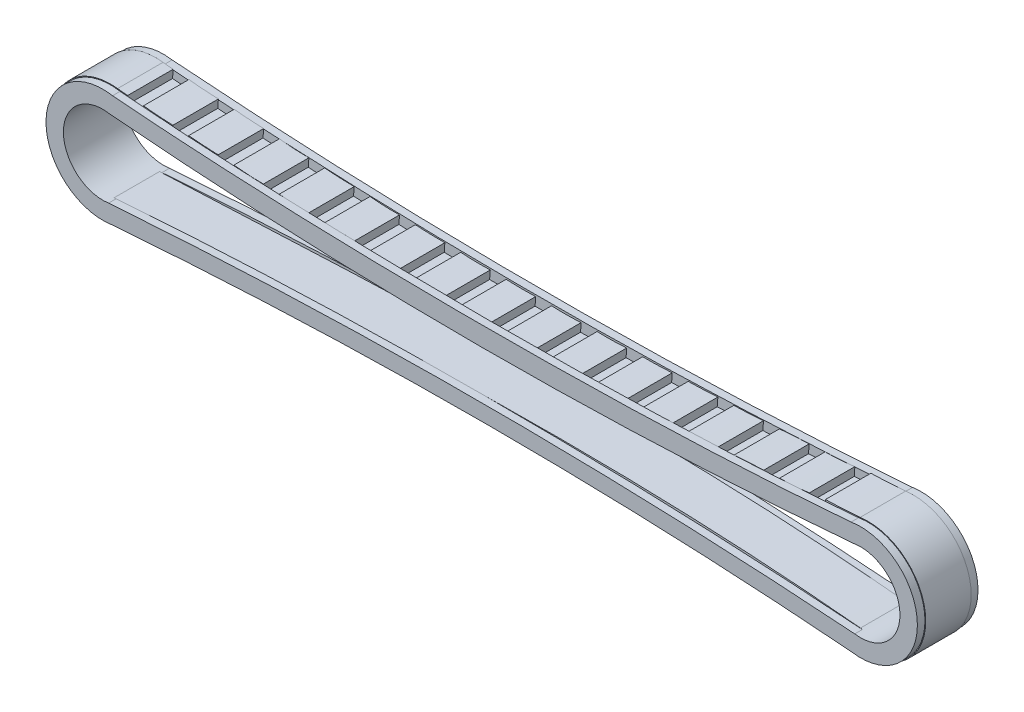
SolidWorks part; units mm, degrees
ref_plane "Front Plane" through (0, 0, 0) normal (0, 0, 1) x (1, 0, 0)
ref_plane "Top Plane" through (0, 0, 0) normal (0, 1, 0) x (1, 0, 0)
ref_plane "Right Plane" through (0, 0, 0) normal (1, 0, 0) x (0, 0, -1)
sketch "Sketch2" plane through (0, 0, 0) normal (0, 0, 1) x (1, 0, 0)
  line L0 (-1229.0453, 0) -> (-23.5148, 0) construction
  line L1 (0, 91.9794) -> (0, -97.7402) construction
  line L2 (-238.5868, 37.1013) -> (-238.9988, 31.5696)
  line L3 (-19.0453, 21.1981) -> (-19.0453, 24.4396)
  line L4 (-228.5815, 30.8004) -> (-228.1726, 36.4078)
  line L5 (-79.0453, 22.4891) -> (-79.0453, 24.4396)
  line L6 (-49.0453, 21.6706) -> (-49.0453, 24.4396)
  line L7 (10.9547, 21.0829) -> (10.9547, 24.4396)
  line L8 (-0.2495, 14.7795) -> (-0.2496, 14.7776)
  line L9 (130.9547, 24.1644) -> (130.9547, 24.4396)
  line L10 (-208.7416, 35.0228) -> (-209.1594, 29.4132)
  line L11 (-198.7348, 28.6971) -> (-198.3256, 34.3091)
  line L12 (40.9547, 21.3284) -> (40.9547, 24.4396)
  line L13 (70.9547, 21.9309) -> (70.9547, 24.4396)
  line L14 (100.9547, 22.8809) -> (100.9547, 24.4396)
  line L15 (-178.8894, 33.0384) -> (-179.3077, 27.4231)
  line L16 (-168.875, 26.7748) -> (-168.4653, 32.393)
  line L17 (-246.0886, 25.7041) -> (245.6238, 25.6291) construction
  line L18 (-245.2661, 37.704) -> (244.7044, 37.6292) construction
  line L19 (-247.5881, -25.8879) -> (244.925, -25.4999) construction
  line L20 (-149.0216, 31.2639) -> (-149.4404, 25.6411)
  line L21 (-138.999, 25.0749) -> (-138.5887, 30.7013)
  line L22 (-109.0453, 23.6339) -> (-109.0453, 24.4396)
  line L23 (-119.4727, 25.2083) -> (-119.5547, 24.1072)
  line L24 (-247.0779, -37.8875) -> (243.8604, -37.5007) construction
  line L25 (-119.1351, 29.7397) -> (-119.4727, 25.2083)
  line L26 (-109.0453, 24.4396) -> (-108.6928, 29.2733)
  line L27 (221.3507, -29.8697) -> (221.8274, -36.4078)
  line L28 (-89.4727, 25.2083) -> (-89.6477, 22.8577)
  line L29 (211.2517, -34.9327) -> (210.8153, -29.0737)
  line L30 (-89.2273, 28.5023) -> (-89.4727, 25.2083)
  line L31 (-79.0453, 24.4396) -> (-78.7752, 28.1435)
  line L32 (191.1909, -27.6789) -> (191.617, -33.5219)
  line L33 (-59.4727, 25.2083) -> (-59.7174, 21.923)
  line L34 (181.0939, -32.8144) -> (180.6592, -26.979)
  line L35 (-59.2958, 27.5822) -> (-59.4727, 25.2083)
  line L36 (-49.0453, 24.4396) -> (-48.8338, 27.34)
  line L37 (161.0517, -25.7703) -> (161.4761, -31.5895)
  line L38 (-29.4727, 25.2083) -> (-29.7618, 21.3263)
  line L39 (150.9576, -30.9848) -> (150.5273, -25.2083)
  line L40 (-29.339, 27.0024) -> (-29.4727, 25.2083)
  line L41 (-19.0453, 24.4396) -> (-18.8671, 26.8832)
  line L42 (10.9547, 14.7776) -> (10.9547, 14.7844)
  line L43 (0.5273, 25.2083) -> (0.22, 21.0827)
  line L44 (-0.2496, 14.7776) -> (10.9547, 14.7776)
  line L45 (0.6443, 26.7781) -> (0.5273, 25.2083)
  line L46 (10.9547, 24.4396) -> (11.1257, 26.7849)
  line L47 (150.5273, -25.2083) -> (150.5248, -25.1736)
  line L48 (30.5273, 25.2083) -> (30.2287, 21.1993)
  line L49 (130.9547, -24.4396) -> (131.3571, -29.9585)
  line L50 (30.6545, 26.9158) -> (30.5273, 25.2083)
  line L51 (40.9547, 24.4396) -> (41.145, 27.0493)
  line L52 (120.8443, -29.4634) -> (120.5273, -25.2083)
  line L53 (60.5273, 25.2083) -> (60.2642, 21.6757)
  line L54 (120.5273, -25.2083) -> (120.4132, -23.6764)
  line L55 (60.6917, 27.4148) -> (60.5273, 25.2083)
  line L56 (70.9547, 24.4396) -> (71.1905, 27.6732)
  line L57 (100.9547, -24.4396) -> (101.2615, -28.6474)
  line L58 (90.5273, 25.2083) -> (90.326, 22.5053)
  line L59 (90.7553, -28.2681) -> (90.5273, -25.2083)
  line L60 (90.7553, 28.2681) -> (90.5273, 25.2083)
  line L61 (100.9547, 24.4396) -> (101.2615, 28.6474)
  line L62 (90.5273, -25.2083) -> (90.326, -22.5053)
  line L63 (120.5273, 25.2083) -> (120.4132, 23.6764)
  line L64 (70.9547, -24.4396) -> (71.1905, -27.6732)
  line L65 (120.8443, 29.4634) -> (120.5273, 25.2083)
  line L66 (130.9547, 24.4396) -> (131.3571, 29.9585)
  line L67 (60.6917, -27.4148) -> (60.5273, -25.2083)
  line L68 (150.5273, 25.2083) -> (150.5248, 25.1736)
  line L69 (60.5273, -25.2083) -> (60.2642, -21.6757)
  line L70 (150.9576, 30.9848) -> (150.5273, 25.2083)
  line L71 (161.0517, 25.7703) -> (161.4761, 31.5895)
  line L72 (40.9547, -24.4396) -> (41.145, -27.0493)
  line L73 (30.6545, -26.9158) -> (30.5273, -25.2083)
  line L74 (30.5273, -25.2083) -> (30.2287, -21.1993)
  line L75 (181.0939, 32.8144) -> (180.6592, 26.979)
  line L76 (191.1909, 27.6789) -> (191.617, 33.5219)
  line L77 (10.9547, -24.4396) -> (11.1257, -26.7849)
  line L78 (0.6443, -26.7781) -> (0.5273, -25.2083)
  line L79 (-0.2496, -14.7776) -> (0, -14.7776)
  line L80 (211.2517, 34.9327) -> (210.8153, 29.0737)
  line L81 (221.3507, 29.8697) -> (221.8274, 36.4078)
  line L82 (221.3507, -29.8697) -> (221.8274, -36.4078)
  line L83 (0.5273, -25.2083) -> (0.22, -21.0827)
  line L84 (-245.2661, -37.704) -> (-247.0779, -37.8875)
  line L85 (10.9547, -14.7776) -> (10.9547, -14.7844)
  line L87 (-19.0453, -24.4396) -> (-18.8671, -26.8832)
  line L88 (-29.339, -27.0024) -> (-29.4727, -25.2083)
  line L89 (-29.4727, -25.2083) -> (-29.7618, -21.3263)
  line L90 (-49.0453, -24.4396) -> (-48.8338, -27.34)
  line L91 (-59.2958, -27.5822) -> (-59.4727, -25.2083)
  line L92 (-59.4727, -25.2083) -> (-59.7174, -21.923)
  line L93 (-79.0453, -24.4396) -> (-78.7752, -28.1435)
  line L94 (-89.2273, -28.5023) -> (-89.4727, -25.2083)
  line L95 (-89.4727, -25.2083) -> (-89.6477, -22.8577)
  line L96 (-109.0453, -24.4396) -> (-108.6928, -29.2733)
  line L97 (-119.1351, -29.7397) -> (-119.4727, -25.2083)
  line L98 (-119.4727, -25.2083) -> (-119.5547, -24.1072)
  line L99 (-109.0453, -23.6339) -> (-109.0453, -24.4396)
  line L100 (-138.999, -25.0749) -> (-138.5887, -30.7013)
  line L101 (-149.0216, -31.2639) -> (-149.4404, -25.6411)
  line L102 (-168.875, -26.7748) -> (-168.4653, -32.393)
  line L103 (-178.8894, -33.0384) -> (-179.3077, -27.4231)
  line L104 (100.9547, -22.8809) -> (100.9547, -24.4396)
  line L105 (70.9547, -21.9309) -> (70.9547, -24.4396)
  line L106 (40.9547, -21.3284) -> (40.9547, -24.4396)
  line L107 (-198.7348, -28.6971) -> (-198.3256, -34.3091)
  line L108 (-208.7416, -35.0228) -> (-209.1594, -29.4132)
  line L109 (130.9547, -24.1644) -> (130.9547, -24.4396)
  line L110 (-0.2495, -14.7795) -> (-0.2496, -14.7776)
  line L111 (10.9547, -21.0829) -> (10.9547, -24.4396)
  line L112 (-49.0453, -21.6706) -> (-49.0453, -24.4396)
  line L113 (-79.0453, -22.4891) -> (-79.0453, -24.4396)
  line L114 (-228.5815, -30.8004) -> (-228.1726, -36.4078)
  line L115 (-19.0453, -21.1981) -> (-19.0453, -24.4396)
  line L116 (-238.5868, -37.1013) -> (-238.9988, -31.5696)
  arc A0 (-246.0886, 25.7041) -> (-247.5881, -25.8879) centre (-250, 0) ccw
  arc A1 (245.6238, 25.6291) -> (244.925, -25.4999) centre (250, 0) cw
  arc A2 (244.7044, 37.6292) -> (243.8604, -37.5007) centre (250, 0) cw
  arc A3 (-245.2661, 37.704) -> (-247.0779, -37.8875) centre (-250, 0) ccw
  arc A4 (-245.2661, 37.704) -> (-238.5868, 37.1013) centre (-233.2976, 133.0299) ccw
  arc A5 (-228.1726, 36.4078) -> (-208.7416, 35.0228) centre (-200.4416, 288.4609) ccw
  arc A6 (-198.3256, 34.3091) -> (-178.8894, 33.0384) centre (-168.3509, 343.5164) ccw
  arc A7 (-168.4653, 32.393) -> (-149.0216, 31.2639) centre (-148.9074, 201.2136) ccw
  arc A8 (-138.5887, 30.7013) -> (-119.1351, 29.7397) centre (-117.6946, 256.1426) ccw
  arc A9 (-108.6928, 29.2733) -> (-89.2273, 28.5023) centre (-91.9581, 205.6706) ccw
  arc A10 (-78.7752, 28.1435) -> (-59.2958, 27.5822) centre (-61.3802, 293.5168) ccw
  arc A11 (-48.8338, 27.34) -> (-29.339, 27.0024) centre (-35.9794, 206.5986) ccw
  arc A12 (-18.8671, 26.8832) -> (0.6443, 26.7781) centre (-7.8548, 260.1471) ccw
  arc A13 (11.1257, 26.7849) -> (30.6545, 26.9158) centre (19.9046, 173.9124) ccw
  arc A14 (41.145, 27.0493) -> (60.6917, 27.4148) centre (47.6506, 201.9714) ccw
  arc A15 (71.1905, 27.6732) -> (90.7553, 28.2681) centre (72.8619, 294.7119) ccw
  arc A16 (101.2615, 28.6474) -> (120.8443, 29.4634) centre (96.1057, 387.8004) ccw
  arc A17 (131.3571, 29.9585) -> (150.9576, 30.9848) centre (123.4328, 368.9588) ccw
  arc A18 (161.4761, 31.5895) -> (181.0939, 32.8144) centre (199.5593, -420.6439) cw
  arc A19 (191.617, 33.5219) -> (211.2517, 34.9327) centre (191.5828, 171.3394) ccw
  arc A20 (221.8274, 36.4078) -> (244.7044, 37.6292) centre (204.7048, 571.9767) ccw
  arc A21 (221.8274, -36.4078) -> (244.7044, -37.6292) centre (204.7048, -571.9767) cw
  arc A22 (191.617, -33.5219) -> (211.2517, -34.9327) centre (191.5828, -171.3394) cw
  arc A23 (161.4761, -31.5895) -> (181.0939, -32.8144) centre (199.5593, 420.6439) ccw
  arc A24 (131.3571, -29.9585) -> (150.9576, -30.9848) centre (123.4328, -368.9588) cw
  arc A25 (101.2615, -28.6474) -> (120.8443, -29.4634) centre (96.1057, -387.8004) cw
  arc A26 (71.1905, -27.6732) -> (90.7553, -28.2681) centre (72.8619, -294.7119) cw
  arc A27 (41.145, -27.0493) -> (60.6917, -27.4148) centre (47.6506, -201.9714) cw
  arc A28 (11.1257, -26.7849) -> (30.6545, -26.9158) centre (19.9046, -173.9124) cw
  arc A29 (-18.8671, -26.8832) -> (0.6443, -26.7781) centre (-7.8548, -260.1471) cw
  arc A30 (-48.8338, -27.34) -> (-29.339, -27.0024) centre (-35.9794, -206.5986) cw
  arc A31 (-78.7752, -28.1435) -> (-59.2958, -27.5822) centre (-61.3802, -293.5168) cw
  arc A32 (-108.6928, -29.2733) -> (-89.2273, -28.5023) centre (-91.9581, -205.6706) cw
  arc A33 (-138.5887, -30.7013) -> (-119.1351, -29.7397) centre (-117.6946, -256.1426) cw
  arc A34 (-168.4653, -32.393) -> (-149.0216, -31.2639) centre (-148.9074, -201.2136) cw
  arc A35 (-198.3256, -34.3091) -> (-178.8894, -33.0384) centre (-168.3509, -343.5164) cw
  arc A36 (-228.1726, -36.4078) -> (-208.7416, -35.0228) centre (-200.4416, -288.4609) cw
  arc A37 (-245.2661, -37.704) -> (-238.5868, -37.1013) centre (-233.2976, -133.0299) cw
  spline S0 degree 3 poles (-246.0886, 25.7041) (-88.1337, 13.7952) (44.7641, 8.7214) (245.6238, 25.6291) knots 0.008118 0.008118 0.008118 0.008118 0.992866 0.992866 0.992866 0.992866
  spline S1 degree 3 poles (-247.5881, -25.8879) (-61.0378, -17.2128) (82.7351, -9.7409) (244.925, -25.4999) knots 0.004243 0.004243 0.004243 0.004243 0.989734 0.989734 0.989734 0.989734
  spline S2 degree 3 poles (-209.1594, 29.4132) (-205.6758, 29.1704) (-202.2013, 28.9316) (-198.7348, 28.6971) knots 0.083029 0.083029 0.083029 0.083029 0.105207 0.105207 0.105207 0.105207
  spline S3 degree 3 poles (210.8153, -29.0737) (214.3065, -29.3321) (217.8181, -29.5974) (221.3507, -29.8697) knots 0.932687 0.932687 0.932687 0.932687 0.950509 0.950509 0.950509 0.950509
  spline S4 degree 3 poles (-179.3077, 27.4231) (-175.8243, 27.2023) (-172.3471, 26.9861) (-168.875, 26.7748) knots 0.146804 0.146804 0.146804 0.146804 0.169262 0.169262 0.169262 0.169262
  spline S5 degree 3 poles (180.6592, -26.979) (184.1495, -27.2052) (187.6599, -27.4384) (191.1909, -27.6789) knots 0.880503 0.880503 0.880503 0.880503 0.898926 0.898926 0.898926 0.898926
  spline S6 degree 3 poles (-238.9988, 31.5696) (-235.515, 31.3097) (-232.0429, 31.0532) (-228.5815, 30.8004) knots 0.020224 0.020224 0.020224 0.020224 0.042026 0.042026 0.042026 0.042026
  spline S7 degree 3 poles (150.5248, -25.1736) (154.014, -25.3652) (157.5228, -25.5641) (161.0517, -25.7703) knots 0.826602 0.826602 0.826602 0.826602 0.845632 0.845632 0.845632 0.845632
  spline S8 degree 3 poles (-149.4404, 25.6411) (-145.9572, 25.4471) (-142.4771, 25.2583) (-138.999, 25.0749) knots 0.211265 0.211265 0.211265 0.211265 0.233894 0.233894 0.233894 0.233894
  spline S9 degree 3 poles (-119.5547, 24.1072) (-116.0521, 23.9435) (-112.5493, 23.7857) (-109.0453, 23.6339) knots 0.276093 0.276093 0.276093 0.276093 0.298904 0.298904 0.298904 0.298904
  spline S10 degree 3 poles (-89.6477, 22.8577) (-86.1174, 22.7283) (-82.5837, 22.6054) (-79.0453, 22.4891) knots 0.340952 0.340952 0.340952 0.340952 0.363877 0.363877 0.363877 0.363877
  spline S11 degree 3 poles (-59.7174, 21.923) (-56.1671, 21.8318) (-52.6102, 21.7476) (-49.0453, 21.6706) knots 0.405505 0.405505 0.405505 0.405505 0.428373 0.428373 0.428373 0.428373
  spline S12 degree 3 poles (-29.7618, 21.3263) (-26.1998, 21.2761) (-22.628, 21.2333) (-19.0453, 21.1981) knots 0.46943 0.46943 0.46943 0.46943 0.492076 0.492076 0.492076 0.492076
  spline S13 degree 3 poles (0, 21.0832) (3.6382, 21.0751) (7.2894, 21.0749) (10.9547, 21.0829) knots 0.531976 0.531976 0.531976 0.531976 0.554706 0.554706 0.554706 0.554706
  spline S14 degree 3 poles (30.2287, 21.1993) (33.7889, 21.2345) (37.3639, 21.2775) (40.9547, 21.3284) knots 0.594269 0.594269 0.594269 0.594269 0.616033 0.616033 0.616033 0.616033
  spline S15 degree 3 poles (60.2642, 21.6757) (63.8108, 21.753) (67.374, 21.838) (70.9547, 21.9309) knots 0.654732 0.654732 0.654732 0.654732 0.675879 0.675879 0.675879 0.675879
  spline S16 degree 3 poles (90.326, 22.5053) (93.8507, 22.6228) (97.3933, 22.748) (100.9547, 22.8809) knots 0.713672 0.713672 0.713672 0.713672 0.734113 0.734113 0.734113 0.734113
  spline S17 degree 3 poles (120.4132, 23.6764) (123.9081, 23.8316) (127.4216, 23.9943) (130.9547, 24.1644) knots 0.770983 0.770983 0.770983 0.770983 0.790653 0.790653 0.790653 0.790653
  spline S18 degree 3 poles (150.5248, 25.1736) (154.014, 25.3652) (157.5228, 25.5641) (161.0517, 25.7703) knots 0.826602 0.826602 0.826602 0.826602 0.845632 0.845632 0.845632 0.845632
  spline S19 degree 3 poles (180.6592, 26.979) (184.1495, 27.2052) (187.6599, 27.4384) (191.1909, 27.6789) knots 0.880503 0.880503 0.880503 0.880503 0.898926 0.898926 0.898926 0.898926
  spline S20 degree 3 poles (210.8153, 29.0737) (214.3065, 29.3321) (217.8181, 29.5974) (221.3507, 29.8697) knots 0.932687 0.932687 0.932687 0.932687 0.950509 0.950509 0.950509 0.950509
  spline S21 degree 3 poles (120.4132, -23.6764) (123.9081, -23.8316) (127.4216, -23.9943) (130.9547, -24.1644) knots 0.770983 0.770983 0.770983 0.770983 0.790653 0.790653 0.790653 0.790653
  spline S22 degree 3 poles (90.326, -22.5053) (93.8507, -22.6228) (97.3933, -22.748) (100.9547, -22.8809) knots 0.713672 0.713672 0.713672 0.713672 0.734113 0.734113 0.734113 0.734113
  spline S23 degree 3 poles (60.2642, -21.6757) (63.8108, -21.753) (67.374, -21.838) (70.9547, -21.9309) knots 0.654732 0.654732 0.654732 0.654732 0.675879 0.675879 0.675879 0.675879
  spline S24 degree 3 poles (30.2287, -21.1993) (33.7889, -21.2345) (37.3639, -21.2775) (40.9547, -21.3284) knots 0.594269 0.594269 0.594269 0.594269 0.616033 0.616033 0.616033 0.616033
  spline S25 degree 3 poles (0.22, -21.0827) (3.7854, -21.0751) (7.3632, -21.0751) (10.9547, -21.0829) knots 0.532434 0.532434 0.532434 0.532434 0.554706 0.554706 0.554706 0.554706
  spline S26 degree 3 poles (-29.7618, -21.3263) (-26.1998, -21.2761) (-22.628, -21.2333) (-19.0453, -21.1981) knots 0.46943 0.46943 0.46943 0.46943 0.492076 0.492076 0.492076 0.492076
  spline S27 degree 3 poles (-59.7174, -21.923) (-56.1671, -21.8318) (-52.6102, -21.7476) (-49.0453, -21.6706) knots 0.405505 0.405505 0.405505 0.405505 0.428373 0.428373 0.428373 0.428373
  spline S28 degree 3 poles (-89.6477, -22.8577) (-86.1174, -22.7283) (-82.5837, -22.6054) (-79.0453, -22.4891) knots 0.340952 0.340952 0.340952 0.340952 0.363877 0.363877 0.363877 0.363877
  spline S29 degree 3 poles (-119.5547, -24.1072) (-116.0521, -23.9435) (-112.5493, -23.7857) (-109.0453, -23.6339) knots 0.276093 0.276093 0.276093 0.276093 0.298904 0.298904 0.298904 0.298904
  spline S30 degree 3 poles (-149.4404, -25.6411) (-145.9572, -25.4471) (-142.4771, -25.2583) (-138.999, -25.0749) knots 0.211265 0.211265 0.211265 0.211265 0.233894 0.233894 0.233894 0.233894
  spline S31 degree 3 poles (-238.9988, -31.5696) (-235.515, -31.3097) (-232.0429, -31.0532) (-228.5815, -30.8004) knots 0.020224 0.020224 0.020224 0.020224 0.042026 0.042026 0.042026 0.042026
  spline S32 degree 3 poles (-179.3077, -27.4231) (-175.8243, -27.2023) (-172.3471, -26.9861) (-168.875, -26.7748) knots 0.146804 0.146804 0.146804 0.146804 0.169262 0.169262 0.169262 0.169262
  spline S33 degree 3 poles (-209.1594, -29.4132) (-205.6758, -29.1704) (-202.2013, -28.9316) (-198.7348, -28.6971) knots 0.083029 0.083029 0.083029 0.083029 0.105207 0.105207 0.105207 0.105207
  point P8 (0, 0)
  dimension "D1" = 12
  dimension "D3" = 16
extrude "Boss-Extrude1" add sketch "Sketch2" along normal blind 30 contours L108 S33 L107 A35 L103 S32 L102 A34 L101 S30 L100 A33 L97 L98 S29 L99 L96 A32 L94 L95 S28 L113 L93 A31 L91 L92 S27 L112 L90 A30 L88 L89 S26 L115 L87 A29 L78 L83 S25 L111 L77 A28 L73 L74 S24 L106 L72 A27 L67 L69 S23
sketch "Sketch4" plane through (0, 0, 30) normal (0, 0, 1) x (1, 0, 0)
  line L0 (0, 67.3971) -> (0, -88.1131) construction
  arc A0 (-245.4957, 25.6069) -> (-246.1722, -25.7167) centre (-250, 0) ccw
  arc A1 (246.1722, -25.7167) -> (245.4957, 25.6069) centre (250, 0) ccw
  arc A2 (-243.5703, 36.9447) -> (-244.1377, -37.0389) centre (-250, 0) ccw
  arc A3 (243.7275, 36.9717) -> (243.8917, -36.9992) centre (250, 0) cw
  arc A4 (-245.4957, 25.6069) -> (245.4957, 25.6069) centre (0, 2864.3017) ccw
  arc A5 (-246.1722, -25.7167) -> (246.1722, -25.7167) centre (0, -3377.7008) cw
  spline S0 degree 3 poles (-243.5703, 36.9447) (-105.4152, 25.2559) (89.5736, 24.2229) (243.7275, 36.9717) knots 0.015171 0.015171 0.015171 0.015171 0.986774 0.986774 0.986774 0.986774
  spline S1 degree 3 poles (-244.1377, -37.0389) (-87.8917, -24.8899) (75.2176, -23.3474) (243.8917, -36.9992) knots 0.012213 0.012213 0.012213 0.012213 0.988223 0.988223 0.988223 0.988223
extrude "Boss-Extrude2" add sketch "Sketch4" along normal blind 5
sketch "Sketch5" plane through (0, 0, 0) normal (0, 0, -1) x (-1, 0, 0)
  arc A0 (-243.5868, -36.9475) -> (243.5868, -36.9475) centre (0, -2902.1019) cw
  arc A1 (-244.2914, 37.0629) -> (244.2914, 37.0629) centre (0, 3265.3892) ccw
  arc A2 (243.5868, -36.9475) -> (244.2914, 37.0629) centre (250, 0) ccw
  arc A3 (-244.2914, 37.0629) -> (-243.5868, -36.9475) centre (-250, 0) ccw
  arc A4 (-245.1461, 25.5429) -> (-245.9989, -25.6903) centre (-250, 0) ccw
  arc A5 (245.9989, -25.6903) -> (245.1461, 25.5429) centre (250, 0) ccw
  arc A6 (-245.1461, 25.5429) -> (245.1461, 25.5429) centre (0, 2654.7349) ccw
  arc A7 (-245.9989, -25.6903) -> (245.9989, -25.6903) centre (0, -3229.732) cw
extrude "Boss-Extrude3" add sketch "Sketch5" along normal blind 5
